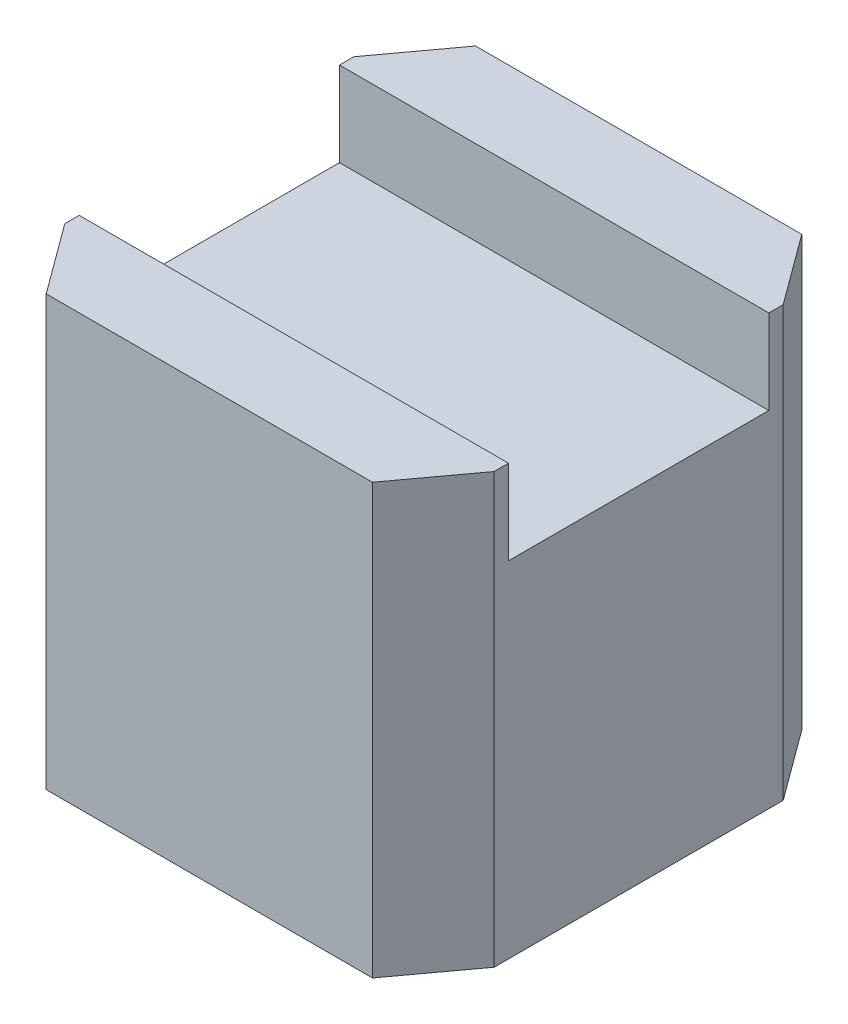
SolidWorks part; units mm, degrees
ref_plane "Спереди" through (0, 0, 0) normal (0, 0, 1) x (1, 0, 0)
ref_plane "Сверху" through (0, 0, 0) normal (0, 1, 0) x (1, 0, 0)
ref_plane "Справа" through (0, 0, 0) normal (1, 0, 0) x (0, 0, -1)
sketch "Эскиз1" plane through (0, 0, 0) normal (0, 1, 0) x (1, 0, 0)
  line L0 (-0.965, 1.27) -> (-1.27, 0.855)
  line L1 (-0.965, 1.27) -> (0.965, 1.27)
  line L2 (-1.27, 0.855) -> (-1.27, -0.855)
  line L3 (-0.965, -1.27) -> (0.965, -1.27)
  line L4 (1.27, 0.855) -> (1.27, -0.855)
  line L5 (0.965, 1.27) -> (1.27, 0.855)
  line L6 (1.27, -0.855) -> (0.965, -1.27)
  line L7 (-1.27, -0.855) -> (-0.965, -1.27)
  point P4 (1.27, 0)
  point P6 (0, 1.27)
  dimension "D1" = 2.54
  dimension "D2" = 2.54
  dimension "D3" = 1.71
  dimension "D4" = 1.93
extrude "Бобышка-Вытянуть1" add sketch "Эскиз1" along normal blind 2.54
sketch "Эскиз2" plane through (0, 2.54, 0) normal (0, 1, 0) x (1, 0, 0)
  line L0 (-1.27, 0.855) -> (-1.27, -0.855) construction
  line L1 (-1.27, 0.77) -> (1.27, 0.77)
  line L2 (-1.27, 0.77) -> (-1.27, -0.77)
  line L3 (-1.27, -0.77) -> (1.27, -0.77)
  line L4 (1.27, 0.77) -> (1.27, -0.77)
  line L5 (1.27, -0.855) -> (1.27, 0.855) construction
  point P8 (-1.27, 0)
  dimension "D1" = 1.54
extrude "Вырез-Вытянуть1" cut sketch "Эскиз2" against normal blind 0.5
